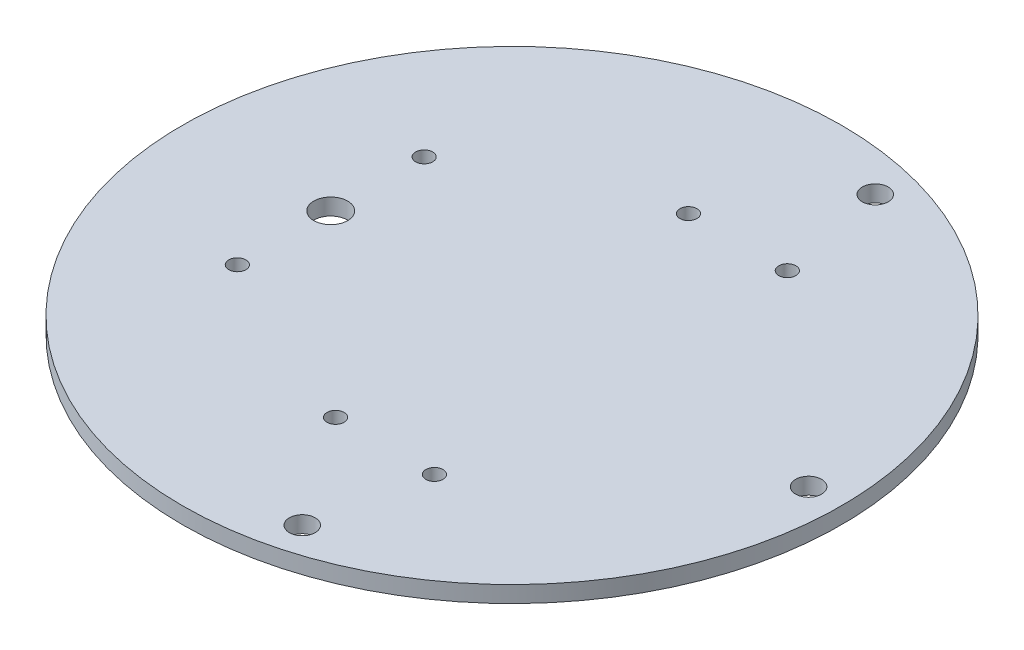
SolidWorks part; units mm, degrees
material "Plain Carbon Steel"
ref_plane "Front Plane" through (0, 0, 0) normal (0, 0, 1) x (1, 0, 0)
ref_plane "Top Plane" through (0, 0, 0) normal (0, 1, 0) x (1, 0, 0)
ref_plane "Right Plane" through (0, 0, 0) normal (1, 0, 0) x (0, 0, -1)
sketch "Sketch1" plane through (0, 0, 0) normal (0, 1, 0) x (1, 0, 0)
  circle A0 centre (0, 0) radius 63.5
  dimension "D1" = 127
extrude "Boss-Extrude1" add sketch "Sketch1" along normal blind 3.175
hole_wizard "Tap Drill for M4x0.7 Tap1" positions "Sketch6" profile "Sketch7" hole size "M4x0.7" standard "ANSI Metric" end condition through all
sketch "Sketch6" plane through (0, 3.175, 0) normal (0, 1, 0) x (1, 0, 0)
  line L0 (0, 34) -> (0, -34) construction
  point P1 (0, 34)
  point P2 (0, -34)
  point P5 (0, 0)
  dimension "D1" = 68
sketch "Sketch7" plane through (0, 3.175, -34) normal (1, 0, 0) x (0, 0, 1)
  line L0 (0, 0) -> (0, 3.175)
  line L1 (0, 3.175) -> (1.65, 3.175)
  line L2 (1.65, 3.175) -> (1.65, 0)
  line L5 (1.65, 0) -> (0, 0)
  line L11 (0, -6.35) -> (0, 107.95) construction
  dimension "Thru Hole Dia." = 3.3
  dimension "Thru Hole Depth" = 3.175
sketch "Sketch8" plane through (0, 3.175, 0) normal (0, 1, 0) x (1, 0, 0)
  line L0 (14.7915, 55.2027) -> (0, 0) construction
  line L1 (0, 0) -> (14.7915, -55.2027) construction
  line L2 (0, 0) -> (57.15, 0) construction
  point P0 (57.15, 0)
  point P1 (14.7915, 55.2027)
  point P2 (14.7915, -55.2027)
  dimension "D1" = 75
  dimension "D2" = 75
  dimension "D3" = 57.15
sketch "Sketch11" plane through (0, 3.175, 0) normal (0, 1, 0) x (1, 0, 0)
  point P0 (14.7915, 55.2027)
  point P3 (57.15, 0)
  point P6 (14.7915, -55.2027)
hole_wizard "#9 (0.196) Diameter Hole1" positions "Sketch11" profile "Sketch10" hole size "#9" standard "ANSI Inch" end condition through all
sketch "Sketch10" plane through (14.7915, 3.175, -55.2027) normal (1, 0, 0) x (0, 0, 1)
  line L0 (0, 0) -> (0, 3.175)
  line L1 (0, 3.175) -> (2.4892, 3.175)
  line L2 (2.4892, 3.175) -> (2.4892, 0)
  line L5 (2.4892, 0) -> (0, 0)
  line L11 (0, -6.35) -> (0, 107.95) construction
  dimension "Thru Hole Dia." = 4.9784
  dimension "Thru Hole Depth" = 3.175
sketch "Sketch12" plane through (0, 3.175, 0) normal (0, 1, 0) x (1, 0, 0)
  line L0 (0, 0) -> (57.15, 0) construction
  line L1 (-15.875, -30) -> (-53.975, -30) construction
  line L2 (-15.875, -30) -> (-15.875, 30) construction
  line L3 (-15.875, 30) -> (-53.975, 30) construction
  line L4 (-53.975, -30) -> (-53.975, 30) construction
  line L5 (-15.875, -30) -> (-53.975, 30) construction
  line L6 (-15.875, 30) -> (-53.975, -30) construction
  line L7 (49.05, -30) -> (-10.95, -30) construction
  line L8 (49.05, -30) -> (49.05, 30) construction
  line L9 (49.05, 30) -> (-10.95, 30) construction
  line L10 (-10.95, -30) -> (-10.95, 30) construction
  line L11 (49.05, -30) -> (-10.95, 30) construction
  line L12 (49.05, 30) -> (-10.95, -30) construction
  line L13 (0, 34) -> (19.05, 34) construction
  line L14 (19.05, 34) -> (19.05, 0) construction
  line L15 (19.05, 0) -> (19.05, -34) construction
  line L16 (0, 0) -> (57.15, 0) construction
  circle A0 centre (-34.925, 0) radius 3.2639
  circle A1 centre (-34.925, 18) radius 1.65
  circle A2 centre (-34.925, -18) radius 1.65
  circle A3 centre (19.05, 34) radius 1.65
  circle A4 centre (0, 34) radius 1.65 construction
  circle A5 centre (19.05, -34) radius 1.65
  point P0 (-34.925, 0)
  point P6 (19.05, 0)
  dimension "D5" = 6.5278
  dimension "D6" = 3.3
  dimension "D1" = 38.1
  dimension "D2" = 60
  dimension "D3" = 53.975
  dimension "D4" = 19.05
  dimension "D7" = 18
extrude "Cut-Extrude1" cut sketch "Sketch12" against normal through all both and the other way through all
equation "\"mount distance\"= 2.25"
equation "\"D3@Sketch8\"=\"mount distance\""
